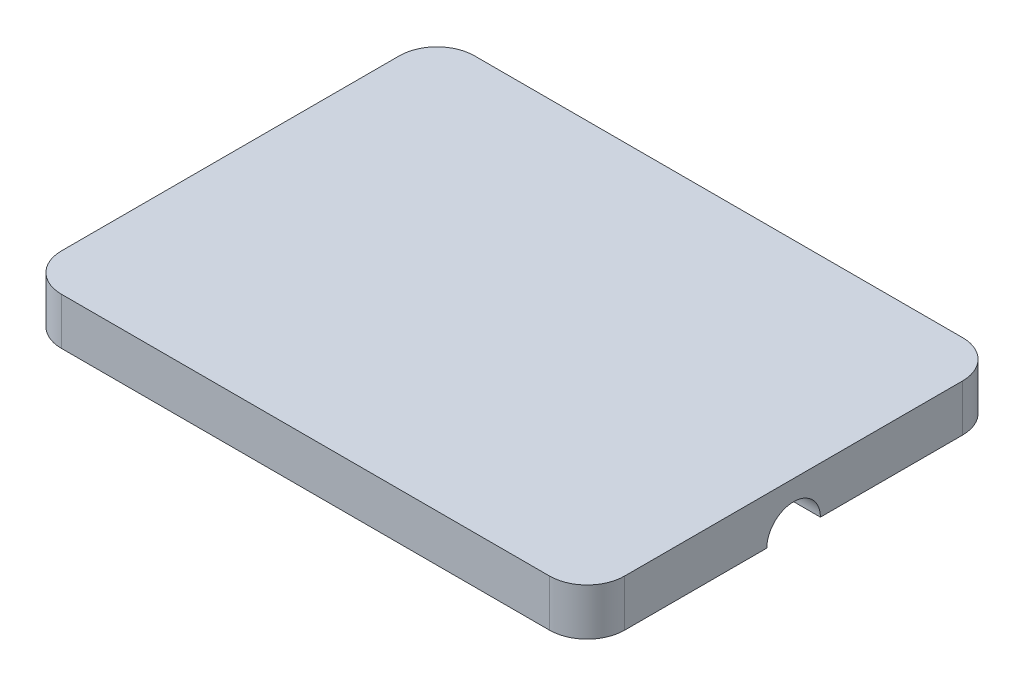
SolidWorks part; units mm, degrees
ref_plane "Front Plane" through (0, 0, 0) normal (0, 0, 1) x (1, 0, 0)
ref_plane "Top Plane" through (0, 0, 0) normal (0, 1, 0) x (1, 0, 0)
ref_plane "Right Plane" through (0, 0, 0) normal (1, 0, 0) x (0, 0, -1)
sketch "Sketch1" plane through (0, 0, 0) normal (0, 1, 0) x (1, 0, 0)
  line L0 (0, 0) -> (300, 0) construction
  line L1 (0, 0) -> (0, 90)
  line L2 (20, 110) -> (280, 110)
  line L3 (300, 90) -> (300, 0)
  line L4 (300, 0) -> (300, -90)
  line L5 (280, -110) -> (20, -110)
  line L6 (0, -90) -> (0, 0)
  arc A0 (20, -110) -> (0, -90) centre (20, -90) cw
  arc A1 (280, -110) -> (300, -90) centre (280, -90) ccw
  arc A2 (280, 110) -> (300, 90) centre (280, 90) cw
  arc A3 (20, 110) -> (0, 90) centre (20, 90) ccw
  dimension "D1" = 20
extrude "Boss-Extrude1" add sketch "Sketch1" along normal blind 25
sketch "Sketch2" plane through (0, 0, 0) normal (1, 0, 0) x (0, 0, -1)
  circle A0 centre (0, 0) radius 14.285
extrude "Cut-Extrude1" cut sketch "Sketch2" along normal through all
